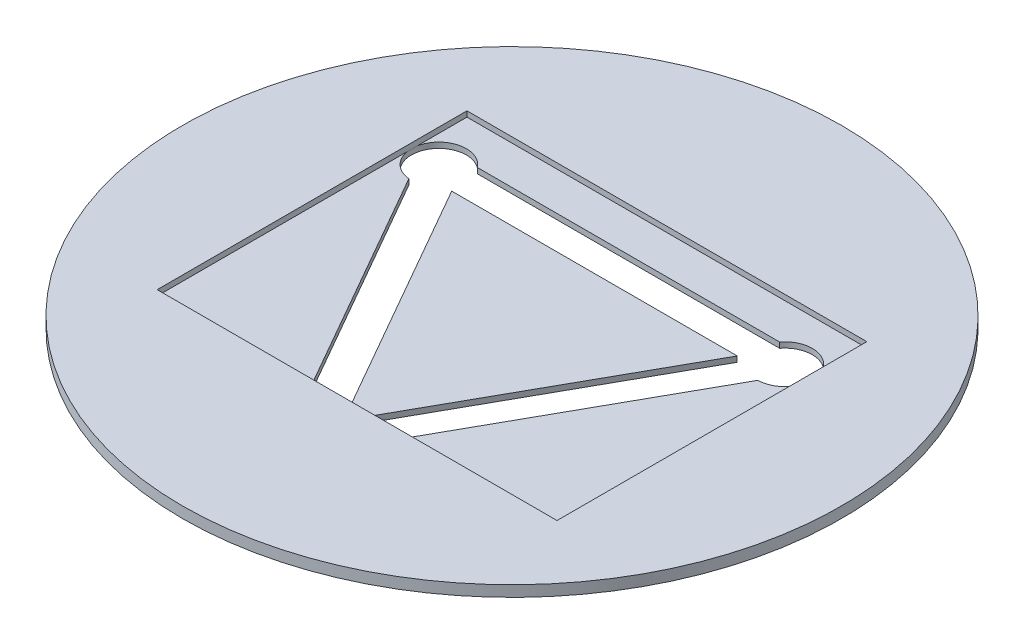
SolidWorks part; units mm, degrees
ref_plane "Front Plane" through (0, 0, 0) normal (0, 0, 1) x (1, 0, 0)
ref_plane "Top Plane" through (0, 0, 0) normal (0, 1, 0) x (1, 0, 0)
ref_plane "Right Plane" through (0, 0, 0) normal (1, 0, 0) x (0, 0, -1)
sketch "Sketch1" plane through (0, 0, 0) normal (0, 1, 0) x (1, 0, 0)
  circle A0 centre (0, 0) radius 150
  dimension "D1" = 300
extrude "Boss-Extrude1" add sketch "Sketch1" along normal blind 5
sketch "Sketch2" plane through (0, 0, 0) normal (0, -1, 0) x (1, 0, 0)
  line L0 (0, 0) -> (0, 78.4072) construction
  circle A1 centre (0, 90.9072) radius 12.5
  circle A2 centre (78.728, -45.4536) radius 12.5
  circle A3 centre (-78.728, -45.4536) radius 12.5
  point P7 (0, 106.9509)
  point P11 (0, 0)
  point P12 (0, 104.6017)
  point P13 (0, 90.9072)
  dimension "D1" = 45
  dimension "D2" = 3
extrude "Cut-Extrude1" cut sketch "Sketch2" against normal blind 2.5
sketch "Sketch4" plane through (0, 5, 0) normal (0, 1, 0) x (1, 0, 0)
  line L1 (-91, -70.5) -> (91, -70.5)
  line L2 (-91, -70.5) -> (-91, 70.5)
  line L3 (-91, 70.5) -> (91, 70.5)
  line L4 (91, -70.5) -> (91, 70.5)
  line L5 (-91, -70.5) -> (91, 70.5) construction
  line L6 (-91, 70.5) -> (91, -70.5) construction
  point P0 (0, 0)
  dimension "D1" = 182
  dimension "D2" = 141
extrude "Cut-Extrude2" cut sketch "Sketch4" against normal blind 2.5
sketch "Sketch5" plane through (0, 0, 0) normal (0, -1, 0) x (1, 0, 0)
  line L0 (-11.6593, 86.4005) -> (-79.9556, -33.014)
  line L1 (0.4848, 77.1688) -> (-65.3153, -37.8812)
  line L2 (-65.3153, -37.8812) -> (64.6424, -37.8812)
  line L3 (-68.7827, -53.026) -> (68.7827, -53.026)
  line L4 (0.4848, 77.1688) -> (64.6424, -37.8812)
  line L5 (78.9347, -32.9553) -> (11.935, 87.1915)
  circle A0 centre (0, 90.9072) radius 12.5 construction
  arc A1 (-11.6593, 86.4005) -> (11.935, 87.1915) centre (0, 90.9072) ccw
  circle A3 centre (-78.728, -45.4536) radius 12.5 construction
  circle A4 centre (0, 90.9072) radius 12.5 construction
  circle A5 centre (78.728, -45.4536) radius 12.5 construction
  arc A6 (-68.7827, -53.026) -> (-79.9556, -33.014) centre (-78.728, -45.4536) ccw
  arc A7 (78.9347, -32.9553) -> (68.7827, -53.026) centre (78.728, -45.4536) ccw
  dimension "D2" = 15.125
extrude "Cut-Extrude3" cut sketch "Sketch5" against normal blind 2.5
